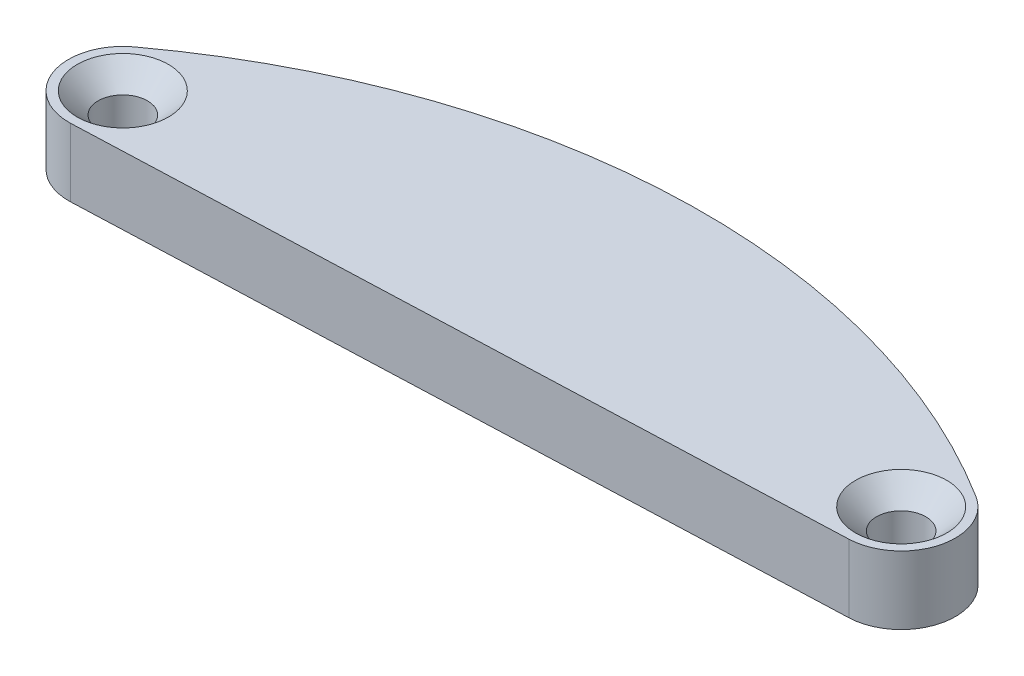
SolidWorks part; units mm, degrees
ref_plane "Front" through (0, 0, 0) normal (0, 0, 1) x (1, 0, 0)
ref_plane "Top" through (0, 0, 0) normal (0, 1, 0) x (1, 0, 0)
ref_plane "Right" through (0, 0, 0) normal (1, 0, 0) x (0, 0, -1)
sketch "Sketch1" plane through (0, 0, 0) normal (0, 1, 0) x (1, 0, 0)
  line L0 (-27.1864, 33.2528) -> (24.5375, 35.2528)
  arc A0 (-27.3313, 37) -> (24.3926, 39) centre (0, 0) cw construction
  arc A1 (-27.3313, -37) -> (24.3926, -39) centre (0, 0) ccw construction
  arc A2 (-29.5594, 40.0163) -> (26.3812, 42.1793) centre (0, 0) cw
  arc A3 (-29.5594, 40.0163) -> (-27.1864, 33.2528) centre (-27.3313, 37) ccw
  arc A4 (26.3812, 42.1793) -> (24.5375, 35.2528) centre (24.3926, 39) cw
  dimension "D1" = 46
  dimension "D4" = 3.75
  dimension "D2" = 74
  dimension "D3" = 78
extrude "Boss-Extrude1" add sketch "Sketch1" along normal blind 4.699
hole_wizard "CSK for M3 Flat Head Machine Screw1" positions "Sketch2" profile "Sketch3" countersink size "M3" standard "ANSI Metric" end condition through all
sketch "Sketch2" plane through (0, 4.699, 0) normal (0, 1, 0) x (1, 0, 0)
  point P0 (-27.3313, 37)
  point P3 (24.3926, 39)
sketch "Sketch3" plane through (-27.3313, 4.699, -37) normal (1, 0, 0) x (0, 0, 1)
  line L0 (0, 0) -> (0, 4.699)
  line L1 (0, 4.699) -> (1.7, 4.699)
  line L2 (1.7, 4.699) -> (1.7, 1.45)
  line L3 (1.7, 1.45) -> (3.15, 0)
  line L5 (3.15, 0) -> (0, 0)
  line L6 (-1.7, 1.45) -> (-3.15, 0) construction
  line L11 (0, -6.35) -> (0, 107.95) construction
  dimension "Thru Hole Dia." = 3.4
  dimension "Thru Hole Depth" = 4.699
  dimension "Near C'Sink Dia." = 6.3
  dimension "Near C'Sink Angle" = 90
